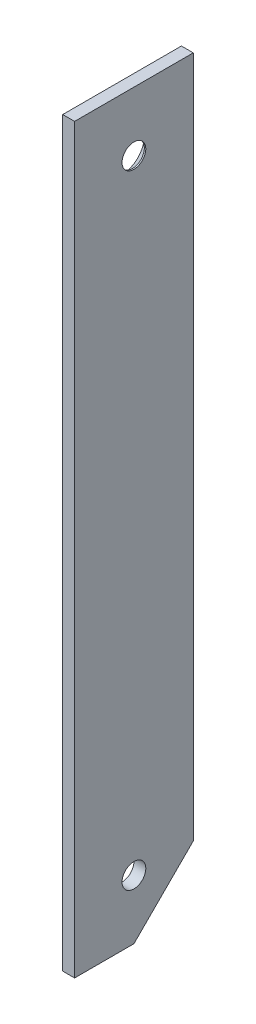
SolidWorks part; units mm, degrees
ref_plane "Front Plane" through (0, 0, 0) normal (0, 0, 1) x (1, 0, 0)
ref_plane "Top Plane" through (0, 0, 0) normal (0, 1, 0) x (1, 0, 0)
ref_plane "Right Plane" through (0, 0, 0) normal (1, 0, 0) x (0, 0, -1)
sketch "Sketch1" plane through (0, 0, 0) normal (1, 0, 0) x (0, 0, -1)
  line L0 (0, 125) -> (0, -125) construction
  line L1 (-20, 125) -> (20, 125)
  line L2 (-20, 125) -> (-20, -125)
  line L3 (-20, -125) -> (20, -125)
  line L4 (20, 125) -> (20, -125)
  line L5 (-20, 125) -> (20, -125) construction
  line L6 (-20, -125) -> (20, 125) construction
  line L7 (0, 0) -> (45.6121, 0) construction
  circle A0 centre (0, 105) radius 4
  circle A1 centre (0, -105) radius 4
  point P0 (0, 0)
  dimension "D3" = 20
  dimension "D1" = 125
  dimension "D2" = 40
  dimension "D4" = 125
  dimension "D6" = 20
  dimension "D7" = 20
  dimension "D8" = 20
extrude "Boss-Extrude1" add sketch "Sketch1" along normal blind 4
chamfer "Chamfer1" distance 3.5 angle 45 1 edges at (0, 105, -4)
chamfer "Chamfer3" distance 20 angle 45 1 edges at (2, -125, -20)
